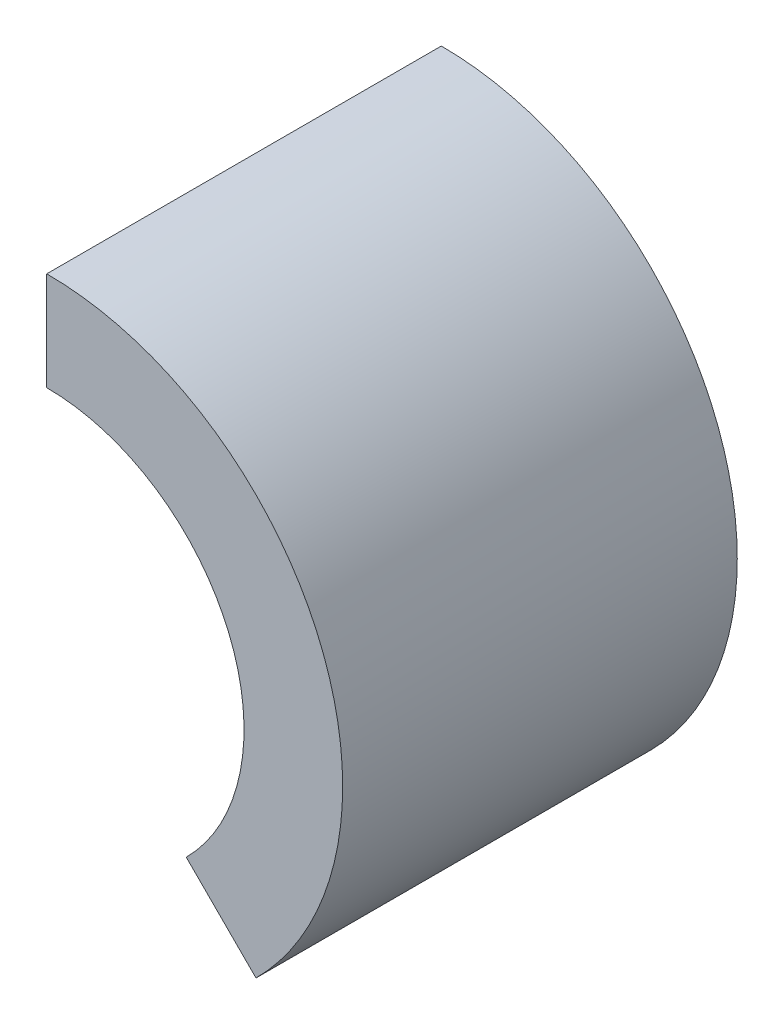
SolidWorks part; units mm, degrees
ref_plane "Alzado" through (0, 0, 0) normal (0, 0, 1) x (1, 0, 0)
ref_plane "Planta" through (0, 0, 0) normal (0, 1, 0) x (1, 0, 0)
ref_plane "Vista lateral" through (0, 0, 0) normal (1, 0, 0) x (0, 0, -1)
sketch "Croquis1" plane through (0, 0, 0) normal (0, 0, 1) x (1, 0, 0)
  line L0 (0, 30) -> (0, 20)
  line L1 (14.1421, -14.1421) -> (21.2132, -21.2132)
  arc A0 (0, 20) -> (14.1421, -14.1421) centre (0, 0) cw
  arc A1 (0, 30) -> (21.2132, -21.2132) centre (0, 0) cw
extrude "Saliente-Extruir1" add sketch "Croquis1" along normal blind 40
